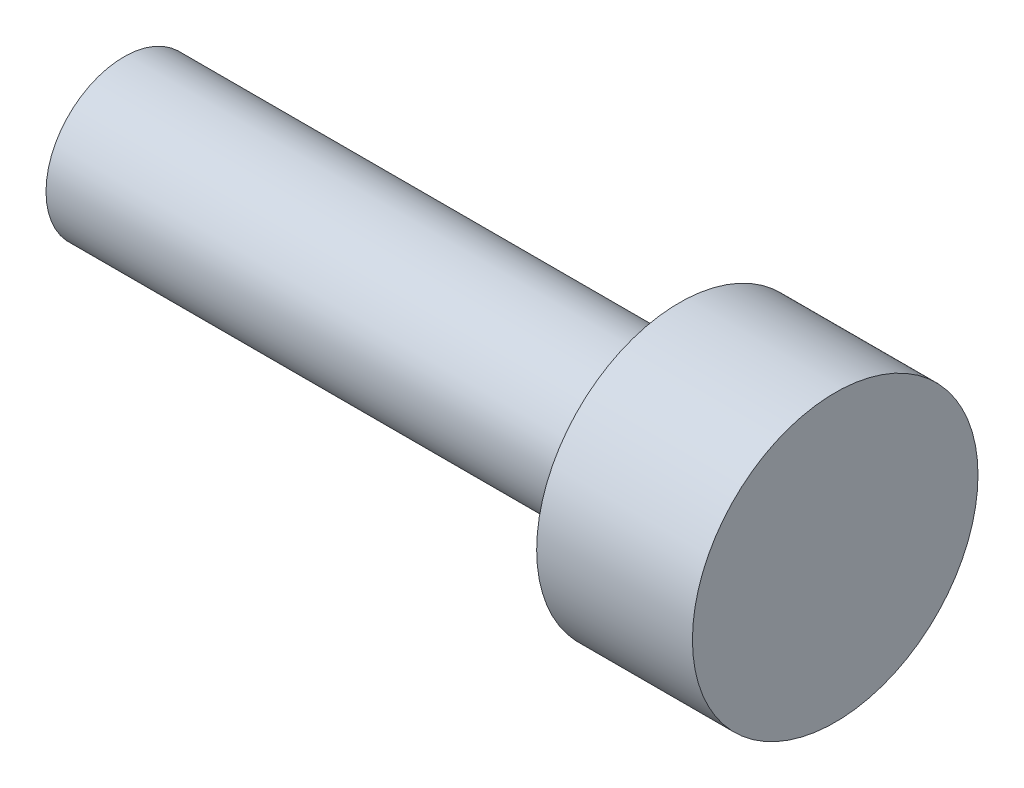
SolidWorks part; units mm, degrees
ref_plane "Front Plane" through (0, 0, 0) normal (0, 0, 1) x (1, 0, 0)
ref_plane "Top Plane" through (0, 0, 0) normal (0, 1, 0) x (1, 0, 0)
ref_plane "Right Plane" through (0, 0, 0) normal (1, 0, 0) x (0, 0, -1)
sketch "Axial profile (mm)" plane through (0, 0, 0) normal (0, 0, 1) x (1, 0, 0)
  line L0 (-110, 0) -> (75, 0) construction
  line L1 (132, 0) -> (145.7, 0)
  line L2 (145.7, 0) -> (145.7, 2.75)
  line L3 (145.7, 2.75) -> (142.7, 2.75)
  line L4 (142.7, 2.75) -> (142.7, 1.5)
  line L5 (142.7, 1.5) -> (132, 1.5)
  line L6 (132, 1.5) -> (132, 0)
revolve "Full revolution" add sketch "Axial profile (mm)" angle 360 about L0
